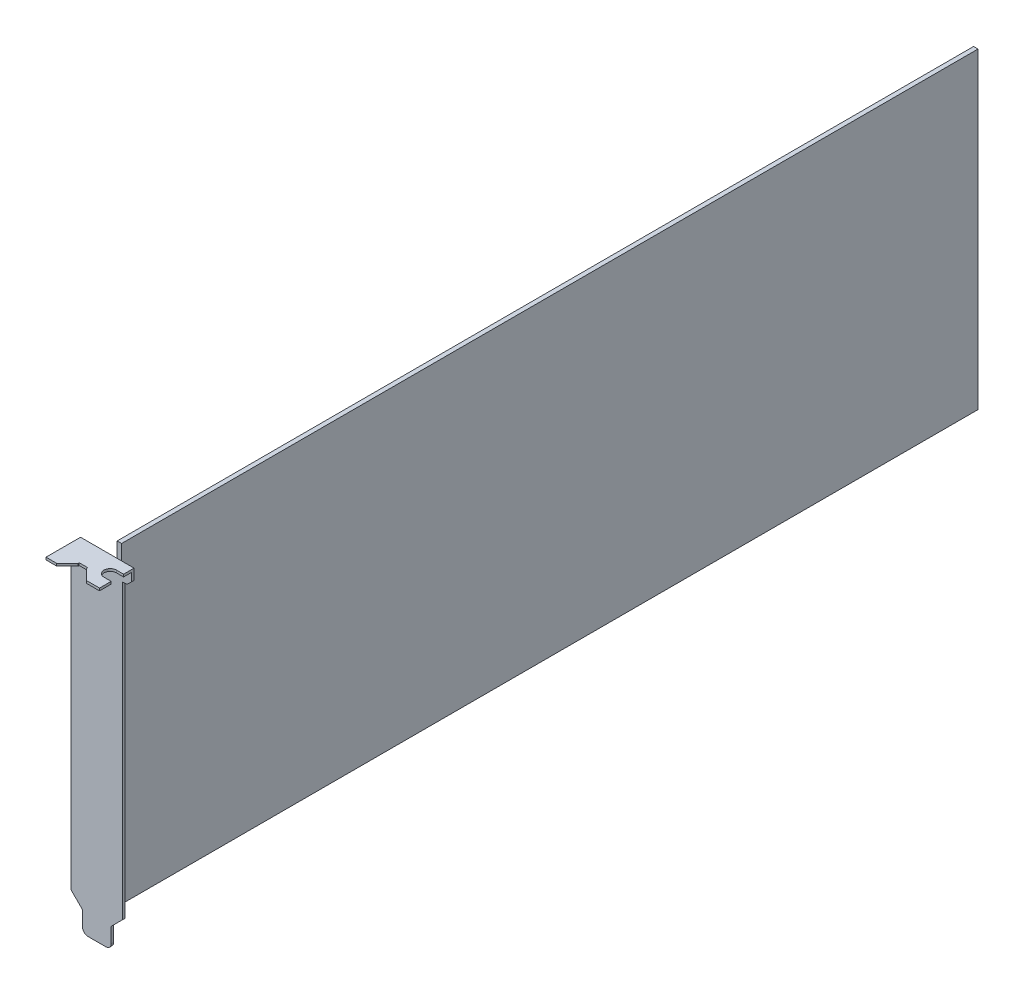
SolidWorks part; units mm, degrees
ref_plane "Front Plane" through (0, 0, 0) normal (0, 0, 1) x (1, 0, 0)
ref_plane "Top Plane" through (0, 0, 0) normal (0, 1, 0) x (1, 0, 0)
ref_plane "Right Plane" through (0, 0, 0) normal (1, 0, 0) x (0, 0, -1)
sketch "Sketch1" plane through (0, 0, 0) normal (0, 0, 1) x (1, 0, 0)
  line L5 (0, 0) -> (1.57, 0)
  line L6 (0, 0) -> (0, 111.15)
  line L7 (0, 111.15) -> (1.57, 111.15)
  line L8 (1.57, 0) -> (1.57, 111.15)
  dimension "D1" = 1.57
  dimension "D2" = 111.15
extrude "pcb" add sketch "Sketch1" along normal blind 304.8
sketch "pcie-opening" plane through (0, 0, 304.8) normal (0, 0, 1) x (1, 0, 0)
  line L0 (0, 111.15) -> (0, 0) construction
  line L1 (-12.41, 94.75) -> (-0.35, 94.75)
  line L2 (-12.41, 94.75) -> (-12.41, 4.85)
  line L3 (-12.41, 4.85) -> (-0.35, 4.85)
  line L4 (-0.35, 94.75) -> (-0.35, 4.85)
  line L5 (1.57, 111.15) -> (0, 111.15) construction
  line L6 (-12.41, 49.8) -> (-0.35, 49.8) construction
  line L7 (-32.73, 94.75) -> (-20.67, 94.75)
  line L8 (-32.73, 94.75) -> (-32.73, 4.85)
  line L9 (-32.73, 4.85) -> (-20.67, 4.85)
  line L10 (-20.67, 94.75) -> (-20.67, 4.85)
  line L11 (-53.05, 94.75) -> (-40.99, 94.75)
  line L12 (-53.05, 94.75) -> (-53.05, 4.85)
  line L13 (-53.05, 4.85) -> (-40.99, 4.85)
  line L14 (-40.99, 94.75) -> (-40.99, 4.85)
  line L15 (-6.38, 94.75) -> (-6.38, 4.85) construction
  dimension "D1" = 0.35
  dimension "D2" = 89.9
  dimension "D3" = 12.06
  dimension "D4" = 16.4
  dimension "D5" = 20.32
  dimension "D6" = 20.32
sketch "mounting-slot" plane through (0, 0, 304.8) normal (0, 0, 1) x (1, 0, 0)
  line L0 (-12.41, 94.75) -> (-0.35, 94.75) construction
  line L1 (-15.58, 104.91) -> (2.84, 104.91)
  line L7 (-15.58, -3.72) -> (-11.46, -7.84)
  line L8 (-15.58, -3.72) -> (-15.58, 104.91)
  line L9 (-1.27, -7.84) -> (2.84, -3.73)
  line L10 (-11.46, -7.84) -> (-11.46, -15.11)
  line L11 (-11.46, -15.11) -> (-1.27, -15.11)
  line L12 (-1.27, -15.11) -> (-1.27, -7.84)
  line L13 (-15.58, -7.84) -> (2.84, -7.84) construction
  line L14 (1.57, 0) -> (1.57, 111.15) construction
  line L15 (2.84, -3.73) -> (2.84, -7.84) construction
  line L16 (-15.58, -3.72) -> (-15.58, -7.84) construction
  line L17 (2.84, 104.91) -> (2.84, 100.35) construction
  line L18 (2.84, 100.35) -> (2.84, -3.73)
  line L19 (2.84, 100.35) -> (6.01, 100.35)
  line L20 (6.01, 100.35) -> (6.01, 104.91)
  line L21 (6.01, 104.91) -> (2.84, 104.91)
  point P6 (-6.38, 94.75)
  dimension "D1" = 10.16
  dimension "D2" = 1.27
  dimension "D3" = 18.42
  dimension "D4" = 112.75
  dimension "D5" = 45
  dimension "D6" = 45
  dimension "D7" = 4.12
  dimension "D8" = 4.11
  dimension "D9" = 120.02
  dimension "D10" = 10.19
  dimension "D11" = 4.56
  dimension "D12" = 21.59
extrude "Boss-Extrude2" add sketch "mounting-slot" along normal blind 0.86
sketch "Sketch5" plane through (0, 0, 305.66) normal (0, 0, 1) x (1, 0, 0)
  line L0 (-15.58, 99.29) -> (-13.04, 101.83)
  line L1 (-15.58, 104.91) -> (-15.58, -3.72) construction
  line L2 (-13.04, 101.83) -> (-13.04, 104.91)
  line L3 (6.01, 104.91) -> (-15.58, 104.91) construction
  line L4 (-13.04, 104.91) -> (-15.58, 104.91)
  line L5 (-15.58, 104.91) -> (-15.58, 99.29)
  dimension "D1" = 45
  dimension "D2" = 3.08
  dimension "D3" = 2.54
extrude "Cut-Extrude1" cut sketch "Sketch5" against normal up to next
sketch "Sketch7" plane through (0, 0, 305.66) normal (0, 0, 1) x (1, 0, 0)
  line L0 (6.01, 104.91) -> (6.01, 101.99) construction
  line L1 (6.01, 100.35) -> (6.01, 104.91) construction
  line L2 (6.01, 101.99) -> (4.37, 100.35)
  line L3 (2.84, 100.35) -> (6.01, 100.35) construction
  line L7 (6.01, 101.99) -> (6.01, 100.35)
  line L8 (6.01, 100.35) -> (4.37, 100.35)
  dimension "D1" = 2.92
  dimension "D2" = 45
extrude "Cut-Extrude2" cut sketch "Sketch7" against normal up to next
fillet "Fillet2" radius 1.27 1 edges at (4.37, 100.35, 305.23)
fillet "Fillet1" radius 1.91 2 edges at (-11.46, -15.11, 305.23) (-1.27, -15.11, 305.23)
sketch "Sketch8" plane through (0, 0, 304.8) normal (0, 0, -1) x (-1, 0, 0)
  line L1 (13.04, 104.91) -> (-6.01, 104.91)
  line L2 (13.04, 104.91) -> (13.04, 105.77)
  line L3 (13.04, 105.77) -> (-6.01, 105.77)
  line L4 (-6.01, 104.91) -> (-6.01, 105.77)
  dimension "D1" = 0.86
extrude "Boss-Extrude4" add sketch "Sketch8" against normal blind 12.29
sketch "Sketch9" plane through (0, 105.77, 0) normal (0, 1, 0) x (1, 0, 0)
  line L0 (-9.23, -317.09) -> (-5.42, -313.28)
  line L1 (-13.04, -317.09) -> (6.01, -317.09) construction
  line L2 (-2.37, -313.28) -> (-2.37, -312.9)
  line L3 (-2.37, -313.28) -> (1.44, -317.09)
  line L4 (-13.04, -317.09) -> (-13.04, -304.8) construction
  line L5 (6.01, -317.09) -> (6.01, -304.8) construction
  line L6 (-13.04, -310.74) -> (-10.495, -310.74) construction
  line L7 (-2.37, -312.9) -> (-5.42, -312.9)
  line L8 (-5.42, -312.9) -> (-5.42, -313.28)
  line L9 (-10.495, -312.95) -> (-13.04, -312.95) construction
  line L10 (-10.495, -308.53) -> (-13.04, -308.53) construction
  line L11 (1.44, -317.09) -> (-9.23, -317.09)
  line L12 (-13.04, -312.95) -> (-13.04, -308.53) construction
  line L13 (6.01, -308.53) -> (3.465, -308.53)
  line L14 (6.01, -312.95) -> (3.465, -312.95)
  line L15 (6.01, -308.53) -> (6.01, -312.95)
  arc A0 (-10.495, -312.95) -> (-10.495, -308.53) centre (-10.495, -310.74) ccw construction
  arc A1 (3.465, -308.53) -> (3.465, -312.95) centre (3.465, -310.74) ccw
  dimension "D7" = 2.21
  dimension "D1" = 7.62
  dimension "D2" = 8.38
  dimension "D3" = 6.35
  dimension "D4" = 0.38
  dimension "D5" = 4.19
  dimension "D6" = 16.505
  dimension "D8" = 45
  dimension "D9" = 45
extrude "Cut-Extrude3" cut sketch "Sketch9" against normal up to next
